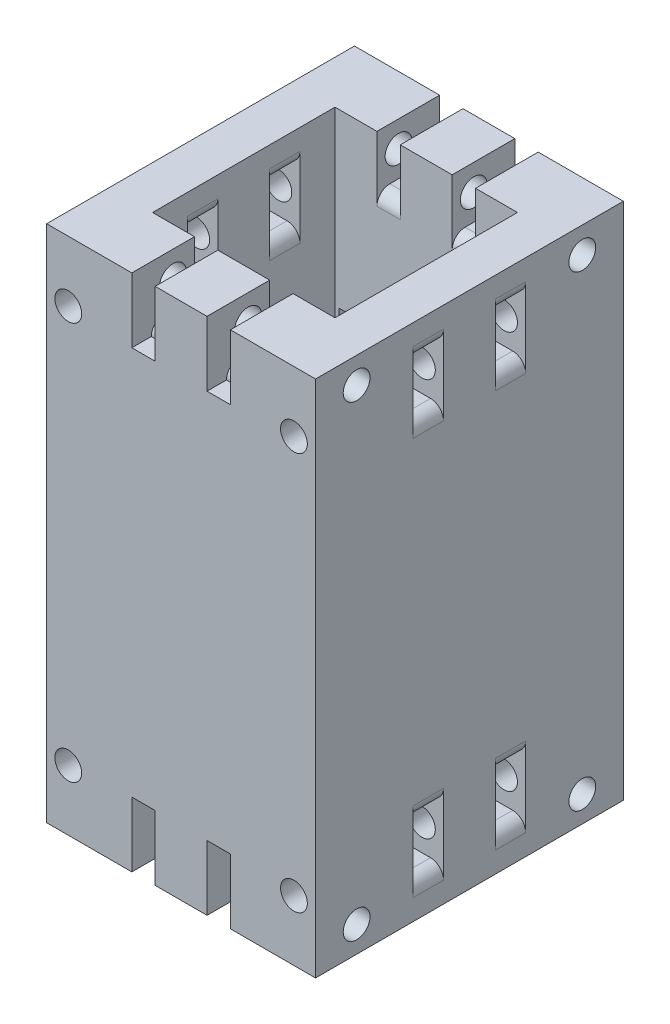
SolidWorks part; units mm, degrees
material "C (石墨)"
ref_plane "前视基准面" through (0, 0, 0) normal (0, 0, 1) x (1, 0, 0)
ref_plane "上视基准面" through (0, 0, 0) normal (0, 1, 0) x (1, 0, 0)
ref_plane "右视基准面" through (0, 0, 0) normal (1, 0, 0) x (0, 0, -1)
other "Configuration Table"
sketch "草图1" plane through (0, 0, 0) normal (0, 1, 0) x (1, 0, 0)
  line L0 (-5, -5) -> (26.1, -5)
  line L1 (0, 0) -> (21.1, 0)
  line L2 (0, 0) -> (0, 21.1)
  line L3 (0, 21.1) -> (21.1, 21.1)
  line L4 (21.1, 0) -> (21.1, 21.1)
  line L5 (26.1, -5) -> (26.1, 26.1)
  line L6 (-5, 26.1) -> (26.1, 26.1)
  line L7 (-5, -5) -> (-5, 26.1)
  dimension "D1" = 21.1
  dimension "D2" = 21.1
  dimension "D3" = 5
extrude "凸台-拉伸1" add sketch "草图1" along normal blind 60
sketch "草图2" plane through (-5, 0, 0) normal (-1, 0, 0) x (0, 0, 1)
  line L0 (-26.1, 60) -> (-26.1, 0) construction
  line L1 (-21.1, 60) -> (-21.1, 0) construction
  line L2 (-26.1, 60) -> (-26.1, 0) construction
  line L3 (-21.1, 60) -> (-21.1, 0) construction
  line L4 (-23.6, 60) -> (-23.6, 0) construction
  line L5 (-26.1, 60) -> (5, 60) construction
  line L6 (-26.1, 0) -> (5, 0) construction
  line L7 (-10.55, 60) -> (-10.55, 0) construction
  circle A0 centre (-23.6, 57) radius 1.55
  circle A1 centre (-23.6, 3) radius 1.55
  circle A2 centre (2.5, 3) radius 1.55
  circle A3 centre (2.5, 57) radius 1.55
  dimension "D4" = 3.1
  dimension "D1" = 2.5
  dimension "D2" = 3
  dimension "D3" = 3
extrude "切除-拉伸1" cut sketch "草图2" against normal through all
sketch "草图3" plane through (0, 0, -21.1) normal (0, 0, 1) x (1, 0, 0)
  line L0 (10.55, 60) -> (10.55, 0) construction
  line L1 (26.1, 30) -> (-5, 30) construction
  line L2 (4.85, 60) -> (7.55, 60)
  line L3 (4.85, 60) -> (4.85, 54)
  line L4 (0, 0) -> (21.1, 0)
  line L5 (21.1, 0) -> (21.1, 60)
  line L6 (21.1, 60) -> (0, 60)
  line L7 (0, 60) -> (0, 0)
  line L8 (0, 0) -> (21.1, 0) construction
  line L9 (21.1, 0) -> (21.1, 60) construction
  line L10 (21.1, 60) -> (0, 60) construction
  line L11 (0, 60) -> (0, 0) construction
  line L12 (4.85, 54) -> (7.55, 54)
  line L13 (7.55, 60) -> (7.55, 54)
  line L14 (13.55, 60) -> (16.25, 60)
  line L15 (13.55, 60) -> (13.55, 54)
  line L16 (13.55, 54) -> (16.25, 54)
  line L17 (16.25, 60) -> (16.25, 54)
  line L18 (26.1, 60) -> (26.1, 0) construction
  line L19 (-5, 60) -> (-5, 0) construction
  line L20 (16.25, 0) -> (16.25, 6)
  line L21 (13.55, 6) -> (16.25, 6)
  line L22 (13.55, 0) -> (13.55, 6)
  line L23 (13.55, 0) -> (16.25, 0)
  line L24 (7.55, 0) -> (7.55, 6)
  line L25 (4.85, 6) -> (7.55, 6)
  line L26 (4.85, 0) -> (4.85, 6)
  line L27 (4.85, 0) -> (7.55, 0)
  dimension "D2" = 6
  dimension "D3" = 2.7
  dimension "D4" = 3
  dimension "D1" = 0
extrude "切除-拉伸2" cut sketch "草图3" against normal through all and the other way through all
sketch "草图4" plane through (0, 0, -26.1) normal (0, 0, -1) x (-1, 0, 0)
  line L0 (-23.6, 60) -> (-23.6, 0) construction
  line L1 (-26.1, 60) -> (-16.25, 60) construction
  line L2 (-26.1, 0) -> (-16.25, 0) construction
  line L3 (-26.1, 60) -> (-26.1, 0) construction
  line L4 (-26.1, 30) -> (5, 30) construction
  line L5 (5, 60) -> (5, 0) construction
  line L6 (-10.55, 60) -> (-10.55, 0) construction
  line L7 (-13.55, 60) -> (-7.55, 60) construction
  line L8 (-13.55, 0) -> (-7.55, 0) construction
  circle A0 centre (-23.6, 53) radius 1.55
  circle A1 centre (2.5, 53) radius 1.55
  circle A2 centre (2.5, 7) radius 1.55
  circle A3 centre (-23.6, 7) radius 1.55
  dimension "D2" = 3.1
  dimension "D1" = 2.5
  dimension "D3" = 7
extrude "切除-拉伸3" cut sketch "草图4" against normal through all
sketch "草图5" plane through (21.1, 0, 0) normal (-1, 0, 0) x (0, 0, 1)
  line L0 (-10.55, 60) -> (-10.55, 0) construction
  line L1 (-26.1, 60) -> (5, 60) construction
  line L2 (-26.1, 0) -> (5, 0) construction
  line L3 (-26.1, 53) -> (5, 53) construction
  line L4 (-26.1, 60) -> (-26.1, 0) construction
  line L5 (5, 60) -> (5, 0) construction
  line L6 (5, 30) -> (-26.1, 30) construction
  line L7 (-17.05, 56.1) -> (-13.55, 56.1)
  line L8 (-17.05, 56.1) -> (-17.05, 49.9)
  line L9 (-17.05, 49.9) -> (-13.55, 49.9)
  line L10 (-13.55, 56.1) -> (-13.55, 49.9)
  line L11 (-7.55, 56.1) -> (-4.05, 56.1)
  line L12 (-7.55, 56.1) -> (-7.55, 49.9)
  line L13 (-7.55, 49.9) -> (-4.05, 49.9)
  line L14 (-4.05, 56.1) -> (-4.05, 49.9)
  line L15 (-4.05, 3.9) -> (-4.05, 10.1)
  line L16 (-7.55, 10.1) -> (-4.05, 10.1)
  line L17 (-7.55, 3.9) -> (-7.55, 10.1)
  line L18 (-7.55, 3.9) -> (-4.05, 3.9)
  line L19 (-13.55, 3.9) -> (-13.55, 10.1)
  line L20 (-17.05, 10.1) -> (-13.55, 10.1)
  line L21 (-17.05, 3.9) -> (-17.05, 10.1)
  line L22 (-17.05, 3.9) -> (-13.55, 3.9)
  dimension "D1" = 7
  dimension "D2" = 3
  dimension "D3" = 3.5
  dimension "D4" = 6.2
  dimension "D5" = 6.2
extrude "切除-拉伸4" cut sketch "草图5" against normal through all and the other way through all
ref_plane "基准面1" through (0, 30, 0) normal (0, 1, 0) x (1, 0, 0)
fillet "圆角1" radius 1.5 48 edges at (14.9, 6, 0) (14.9, 6, 5) (6.2, 6, 0) (6.2, 6, 5) (6.2, 6, -21.1) (6.2, 6, -26.1) (14.9, 6, -21.1) (14.9, 6, -26.1) (21.1, 10.1, -15.3) (21.1, 10.1, -5.8) (26.1, 10.1, -15.3) (26.1, 10.1, -5.8) (26.1, 3.9, -15.3) (21.1, 3.9, -15.3) (26.1, 3.9, -5.8) (21.1, 3.9, -5.8) (0, 10.1, -5.8) (0, 10.1, -15.3) (-5, 10.1, -5.8) (-5, 10.1, -15.3) (-5, 3.9, -5.8) (0, 3.9, -5.8) (0, 3.9, -15.3) (-5, 3.9, -15.3) (21.1, 56.1, -5.8) (26.1, 56.1, -5.8) (0, 56.1, -5.8) (0, 56.1, -15.3) (-5, 56.1, -5.8) (-5, 56.1, -15.3) (0, 49.9, -5.8) (0, 49.9, -15.3) (-5, 49.9, -5.8) (-5, 49.9, -15.3) (6.2, 54, -21.1) (14.9, 54, -21.1) (6.2, 54, -26.1) (14.9, 54, -26.1) (26.1, 56.1, -15.3) (21.1, 56.1, -15.3) (21.1, 49.9, -15.3) (21.1, 49.9, -5.8) (26.1, 49.9, -5.8) (14.9, 54, 5) (6.2, 54, 0) (14.9, 54, 0) (6.2, 54, 5) (26.1, 49.9, -15.3)
sketch "草图6" plane through (0, 0, 5) normal (0, 0, 1) x (1, 0, 0)
  line L0 (5.4175, 30) -> (-5.4175, 30) construction
  line L1 (0.45, 40.1) -> (20.65, 40.1)
  line L2 (0.45, 40.1) -> (0.45, 19.9)
  line L3 (0.45, 19.9) -> (20.65, 19.9)
  line L4 (20.65, 40.1) -> (20.65, 19.9)
  line L5 (0.45, 40.1) -> (20.65, 19.9) construction
  line L6 (0.45, 19.9) -> (20.65, 40.1) construction
  line L7 (10.55, 30) -> (26.2189, 30) construction
  line L8 (26.2189, 30) -> (24.6313, 30)
  line L9 (10.55, 30) -> (10.55, 60) construction
  line L10 (7.55, 60) -> (13.55, 60) construction
  point P0 (10.55, 30)
  dimension "D1" = 20.2
  dimension "D2" = 20.2
extrude "切除-拉伸5" cut sketch "草图6" against normal through all contours L4 L1 L2 L3
sketch "草图7" plane through (0, 0, 5) normal (0, 0, 1) x (1, 0, 0)
  line L20 (13.55, 0) -> (13.55, 7.5)
  line L21 (13.55, 7.5) -> (16.25, 7.5)
  line L22 (16.25, 7.5) -> (16.25, 0)
  line L23 (16.25, 0) -> (26.1, 0)
  line L24 (26.1, 0) -> (26.1, 60)
  line L25 (26.1, 60) -> (16.25, 60)
  line L26 (16.25, 60) -> (16.25, 52.5)
  line L27 (16.25, 52.5) -> (13.55, 52.5)
  line L28 (13.55, 52.5) -> (13.55, 60)
  line L29 (13.55, 60) -> (7.55, 60)
  line L30 (7.55, 60) -> (7.55, 52.5)
  line L31 (7.55, 52.5) -> (4.85, 52.5)
  line L32 (4.85, 52.5) -> (4.85, 60)
  line L33 (4.85, 60) -> (-5, 60)
  line L34 (-5, 60) -> (-5, 0)
  line L35 (-5, 0) -> (4.85, 0)
  line L36 (4.85, 0) -> (4.85, 7.5)
  line L37 (4.85, 7.5) -> (7.55, 7.5)
  line L38 (7.55, 7.5) -> (7.55, 0)
  line L39 (7.55, 0) -> (13.55, 0)
  line L40 (13.55, 0) -> (13.55, 7.5)
  line L41 (13.55, 7.5) -> (16.25, 7.5)
  line L42 (16.25, 7.5) -> (16.25, 0)
  line L43 (16.25, 0) -> (26.1, 0)
  line L44 (26.1, 0) -> (26.1, 60)
  line L45 (26.1, 60) -> (16.25, 60)
  line L46 (16.25, 60) -> (16.25, 52.5)
  line L47 (16.25, 52.5) -> (13.55, 52.5)
  line L48 (13.55, 52.5) -> (13.55, 60)
  line L49 (13.55, 60) -> (7.55, 60)
  line L50 (7.55, 60) -> (7.55, 52.5)
  line L51 (7.55, 52.5) -> (4.85, 52.5)
  line L52 (4.85, 52.5) -> (4.85, 60)
  line L53 (4.85, 60) -> (-5, 60)
  line L54 (-5, 60) -> (-5, 0)
  line L55 (-5, 0) -> (4.85, 0)
  line L56 (4.85, 0) -> (4.85, 7.5)
  line L57 (4.85, 7.5) -> (7.55, 7.5)
  line L58 (7.55, 7.5) -> (7.55, 0)
  line L59 (7.55, 0) -> (13.55, 0)
  circle A0 centre (23.6, 7) radius 1.55 construction
  circle A1 centre (23.6, 53) radius 1.55 construction
  circle A2 centre (-2.5, 53) radius 1.55 construction
  circle A3 centre (-2.5, 7) radius 1.55 construction
  circle A4 centre (23.6, 7) radius 1.55
  circle A5 centre (23.6, 53) radius 1.55
  circle A6 centre (-2.5, 53) radius 1.55
  circle A7 centre (-2.5, 7) radius 1.55
  dimension "D1" = 0
sketch "草图8" plane through (0, 0, -26.1) normal (0, 0, -1) x (-1, 0, 0)
  line L20 (-7.55, 7.5) -> (-4.85, 7.5)
  line L21 (-4.85, 7.5) -> (-4.85, 0)
  line L22 (-4.85, 0) -> (5, 0)
  line L23 (5, 0) -> (5, 60)
  line L24 (5, 60) -> (-4.85, 60)
  line L25 (-4.85, 60) -> (-4.85, 52.5)
  line L26 (-4.85, 52.5) -> (-7.55, 52.5)
  line L27 (-7.55, 52.5) -> (-7.55, 60)
  line L28 (-7.55, 60) -> (-13.55, 60)
  line L29 (-13.55, 60) -> (-13.55, 52.5)
  line L30 (-13.55, 52.5) -> (-16.25, 52.5)
  line L31 (-16.25, 52.5) -> (-16.25, 60)
  line L32 (-16.25, 60) -> (-26.1, 60)
  line L33 (-26.1, 60) -> (-26.1, 0)
  line L34 (-26.1, 0) -> (-16.25, 0)
  line L35 (-16.25, 0) -> (-16.25, 7.5)
  line L36 (-16.25, 7.5) -> (-13.55, 7.5)
  line L37 (-13.55, 7.5) -> (-13.55, 0)
  line L38 (-13.55, 0) -> (-7.55, 0)
  line L39 (-7.55, 0) -> (-7.55, 7.5)
  line L40 (-7.55, 7.5) -> (-4.85, 7.5)
  line L41 (-4.85, 7.5) -> (-4.85, 0)
  line L42 (-4.85, 0) -> (5, 0)
  line L43 (5, 0) -> (5, 60)
  line L44 (5, 60) -> (-4.85, 60)
  line L45 (-4.85, 60) -> (-4.85, 52.5)
  line L46 (-4.85, 52.5) -> (-7.55, 52.5)
  line L47 (-7.55, 52.5) -> (-7.55, 60)
  line L48 (-7.55, 60) -> (-13.55, 60)
  line L49 (-13.55, 60) -> (-13.55, 52.5)
  line L50 (-13.55, 52.5) -> (-16.25, 52.5)
  line L51 (-16.25, 52.5) -> (-16.25, 60)
  line L52 (-16.25, 60) -> (-26.1, 60)
  line L53 (-26.1, 60) -> (-26.1, 0)
  line L54 (-26.1, 0) -> (-16.25, 0)
  line L55 (-16.25, 0) -> (-16.25, 7.5)
  line L56 (-16.25, 7.5) -> (-13.55, 7.5)
  line L57 (-13.55, 7.5) -> (-13.55, 0)
  line L58 (-13.55, 0) -> (-7.55, 0)
  line L59 (-7.55, 0) -> (-7.55, 7.5)
  circle A0 centre (-23.6, 7) radius 1.55 construction
  circle A1 centre (2.5, 7) radius 1.55 construction
  circle A2 centre (2.5, 53) radius 1.55 construction
  circle A3 centre (-23.6, 53) radius 1.55 construction
  circle A4 centre (-23.6, 7) radius 1.55
  circle A5 centre (2.5, 7) radius 1.55
  circle A6 centre (2.5, 53) radius 1.55
  circle A7 centre (-23.6, 53) radius 1.55
  dimension "D1" = 0
extrude "凸台-拉伸2" add sketch "草图7" along normal blind 2.25
extrude "凸台-拉伸3" add sketch "草图8" along normal blind 2.25
